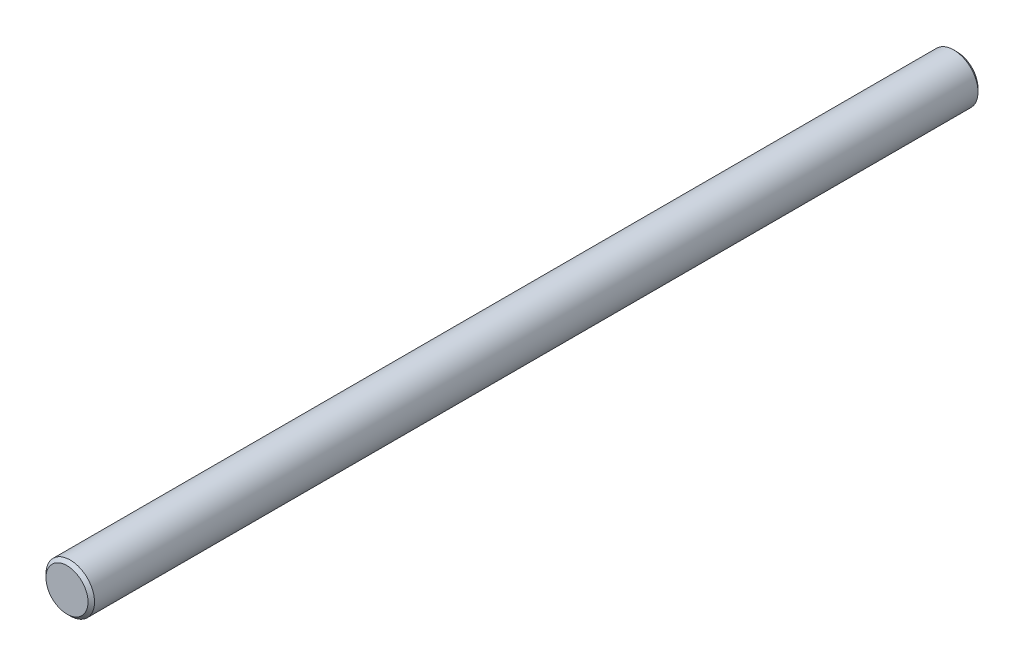
SolidWorks part; units mm, degrees
ref_plane "Front Plane" through (0, 0, 0) normal (0, 0, 1) x (1, 0, 0)
ref_plane "Top Plane" through (0, 0, 0) normal (0, 1, 0) x (1, 0, 0)
ref_plane "Right Plane" through (0, 0, 0) normal (1, 0, 0) x (0, 0, -1)
sketch "Sketch1" plane through (0, 0, 0) normal (0, 0, 1) x (1, 0, 0)
  circle A0 centre (0, 0) radius 1.5
  dimension "D1" = 3
extrude "Boss-Extrude1" add sketch "Sketch1" along normal blind 55
chamfer "Chamfer1" distance 0.2 angle 45 2 edges at (1.5, 0, 55) (1.5, 0, 0)
